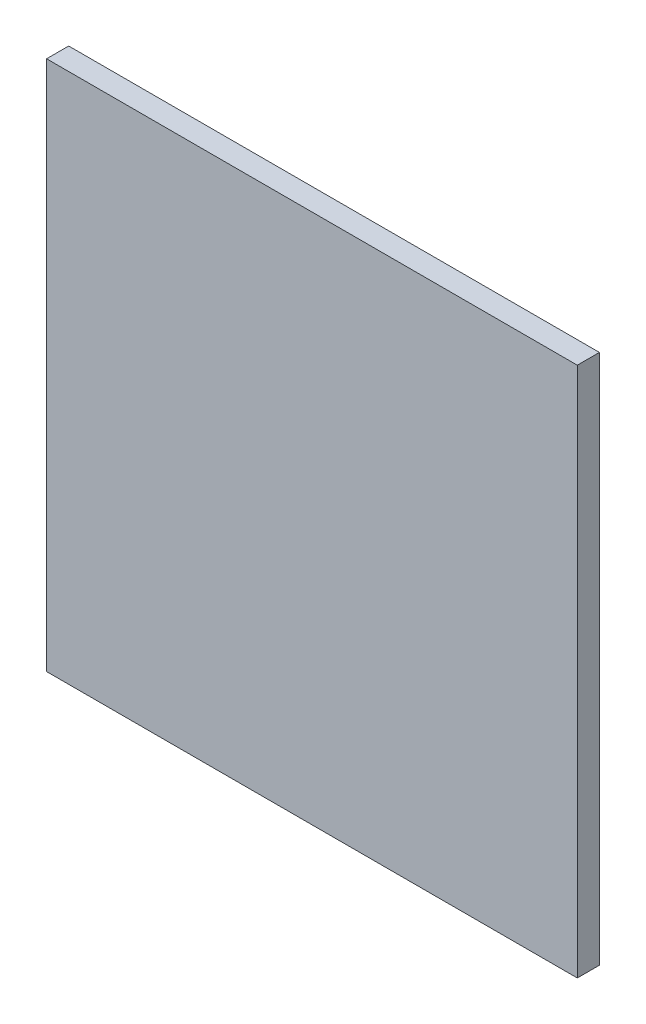
SolidWorks part; units mm, degrees
ref_plane "Front Plane" through (0, 0, 0) normal (0, 0, 1) x (1, 0, 0)
ref_plane "Top Plane" through (0, 0, 0) normal (0, 1, 0) x (1, 0, 0)
ref_plane "Right Plane" through (0, 0, 0) normal (1, 0, 0) x (0, 0, -1)
sketch "Sketch1" plane through (0, 0, 0) normal (0, 0, 1) x (1, 0, 0)
  line L1 (0, 0) -> (609.6, 0)
  line L2 (0, 0) -> (0, 609.6)
  line L3 (0, 609.6) -> (609.6, 609.6)
  line L4 (609.6, 0) -> (609.6, 609.6)
  dimension "D1" = 609.6
extrude "Boss-Extrude1" add sketch "Sketch1" along normal blind 25.4
